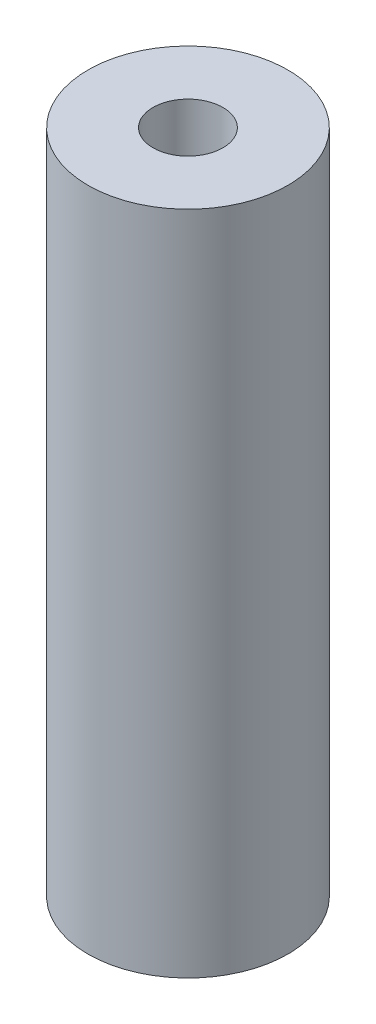
SolidWorks part; units mm, degrees
ref_plane "Front Plane" through (0, 0, 0) normal (0, 0, 1) x (1, 0, 0)
ref_plane "Top Plane" through (0, 0, 0) normal (0, 1, 0) x (1, 0, 0)
ref_plane "Right Plane" through (0, 0, 0) normal (1, 0, 0) x (0, 0, -1)
sketch "Sketch1" plane through (0, 0, 0) normal (0, 1, 0) x (1, 0, 0)
  line L5 (-5, 5) -> (5, -5) construction
  line L6 (-5, -5) -> (5, 5) construction
  circle A0 centre (0, 0) radius 1.75
  circle A5 centre (0, 0) radius 5
  point P0 (0, 0)
  dimension "D2" = 3.5
  dimension "D4" = 10
  dimension "D1" = 10
  dimension "D3" = 10
extrude "Boss-Extrude1" add sketch "Sketch1" along normal blind 33.3
